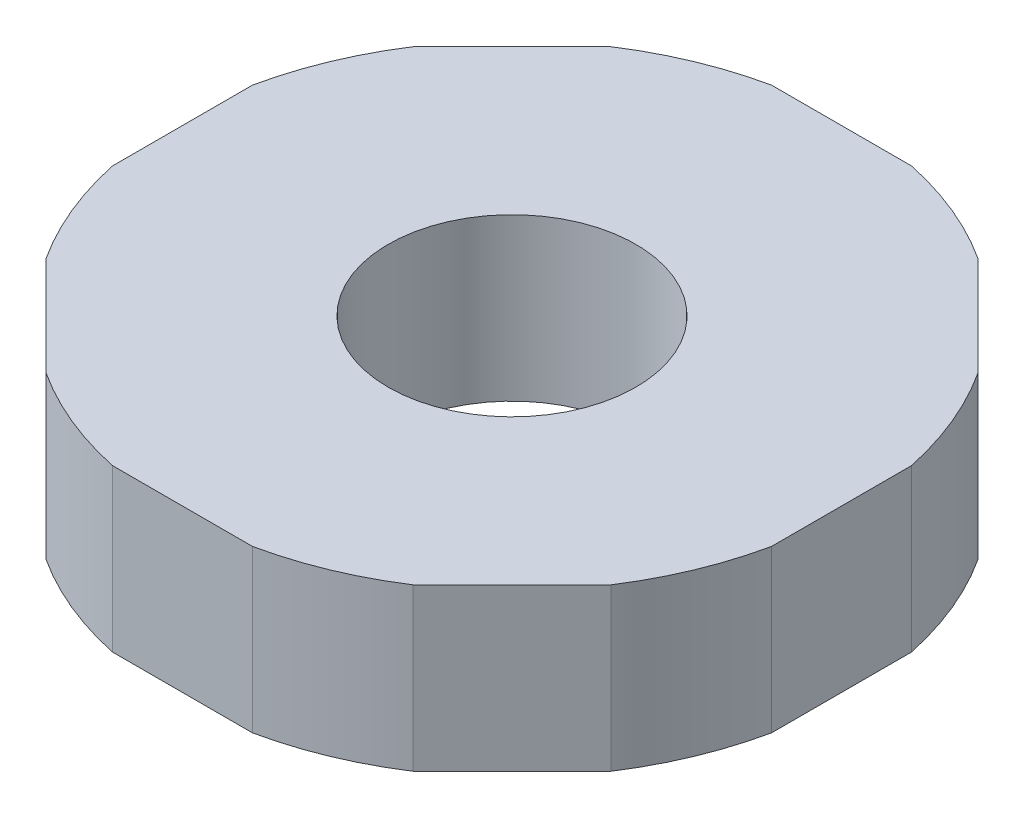
SolidWorks part; units mm, degrees
ref_plane "Front Plane" through (0, 0, 0) normal (0, 0, 1) x (1, 0, 0)
ref_plane "Top Plane" through (0, 0, 0) normal (0, 1, 0) x (1, 0, 0)
ref_plane "Right Plane" through (0, 0, 0) normal (1, 0, 0) x (0, 0, -1)
sketch "Sketch1" plane through (0, 0, 0) normal (0, 1, 0) x (1, 0, 0)
  line L8 (3.4092, -5.2477) -> (5.2477, -3.4092)
  line L9 (6.1213, -1.3) -> (6.1213, 1.3)
  line L10 (5.2477, 3.4092) -> (3.4092, 5.2477)
  line L11 (1.3, 6.1213) -> (-1.3, 6.1213)
  line L12 (-3.4092, 5.2477) -> (-5.2477, 3.4092)
  line L13 (-6.1213, 1.3) -> (-6.1213, -1.3)
  line L14 (-5.2477, -3.4092) -> (-3.4092, -5.2477)
  line L15 (-1.3, -6.1213) -> (1.3, -6.1213)
  line L16 (3.4092, -5.2477) -> (5.2477, -3.4092)
  line L17 (6.1213, -1.3) -> (6.1213, 1.3)
  line L18 (5.2477, 3.4092) -> (3.4092, 5.2477)
  line L19 (1.3, 6.1213) -> (-1.3, 6.1213)
  line L20 (-3.4092, 5.2477) -> (-5.2477, 3.4092)
  line L21 (-6.1213, 1.3) -> (-6.1213, -1.3)
  line L22 (-5.2477, -3.4092) -> (-3.4092, -5.2477)
  line L23 (-1.3, -6.1213) -> (1.3, -6.1213)
  circle A0 centre (0, 0) radius 2.3 construction
  circle A1 centre (0, 0) radius 2.3
  arc A8 (1.3, -6.1213) -> (3.4092, -5.2477) centre (0, 0) ccw
  arc A9 (5.2477, -3.4092) -> (6.1213, -1.3) centre (0, 0) ccw
  arc A10 (6.1213, 1.3) -> (5.2477, 3.4092) centre (0, 0) ccw
  arc A11 (3.4092, 5.2477) -> (1.3, 6.1213) centre (0, 0) ccw
  arc A12 (-1.3, 6.1213) -> (-3.4092, 5.2477) centre (0, 0) ccw
  arc A13 (-5.2477, 3.4092) -> (-6.1213, 1.3) centre (0, 0) ccw
  arc A14 (-6.1213, -1.3) -> (-5.2477, -3.4092) centre (0, 0) ccw
  arc A15 (-3.4092, -5.2477) -> (-1.3, -6.1213) centre (0, 0) ccw
  arc A16 (1.3, -6.1213) -> (3.4092, -5.2477) centre (0, 0) ccw
  arc A17 (5.2477, -3.4092) -> (6.1213, -1.3) centre (0, 0) ccw
  arc A18 (6.1213, 1.3) -> (5.2477, 3.4092) centre (0, 0) ccw
  arc A19 (3.4092, 5.2477) -> (1.3, 6.1213) centre (0, 0) ccw
  arc A20 (-1.3, 6.1213) -> (-3.4092, 5.2477) centre (0, 0) ccw
  arc A21 (-5.2477, 3.4092) -> (-6.1213, 1.3) centre (0, 0) ccw
  arc A22 (-6.1213, -1.3) -> (-5.2477, -3.4092) centre (0, 0) ccw
  arc A23 (-3.4092, -5.2477) -> (-1.3, -6.1213) centre (0, 0) ccw
  dimension "D1" = 0
extrude "Boss-Extrude1" add sketch "Sketch1" against normal blind 3
